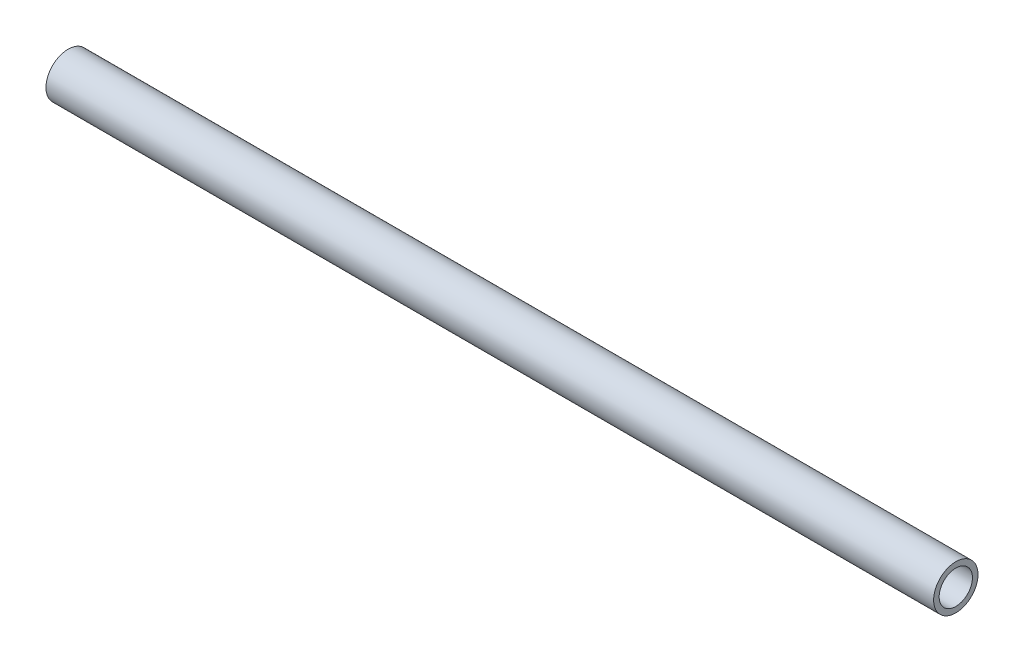
SolidWorks part; units mm, degrees
material "PVC 0.007 Plastificado"
ref_plane "Front" through (0, 0, 0) normal (0, 0, 1) x (1, 0, 0)
ref_plane "Top" through (0, 0, 0) normal (0, 1, 0) x (1, 0, 0)
ref_plane "Right" through (0, 0, 0) normal (1, 0, 0) x (0, 0, -1)
sketch "Sketch1" plane through (0, 0, 0) normal (1, 0, 0) x (0, 0, -1)
  line L0 (4.7625, 0) -> (6.35, 0) construction
  line L1 (4.7625, 0) -> (6.35, 0) construction
  line L2 (5.5562, 0) -> (5.5562, 1.0672) construction
  circle A0 centre (0, 0) radius 6.35
  circle A1 centre (0, 0) radius 4.7625
  point P4 (6.35, 0)
  point P5 (4.7625, 0)
  dimension "OD" = 12.7
  dimension "ID" = 9.525
  dimension "Wall Thickness" = 1.5875
sketch "Sketch2" plane through (0, 0, 0) normal (0, 0, 1) x (1, 0, 0)
  line L0 (-127, 0) -> (127, 0) construction
  point P2 (-111.125, 0)
  point P3 (111.125, 0)
  dimension "D1" = 15.875
  dimension "D2" = 15.875
sketch "Sketch3" plane through (0, 0, 0) normal (1, 0, 0) x (0, 0, -1)
  circle A0 centre (0, 0) radius 4.7625 construction
  circle A1 centre (0, 0) radius 6.35 construction
  circle A2 centre (0, 0) radius 4.7625
  circle A3 centre (0, 0) radius 6.35
extrude "Boss-Extrude1" add sketch "Sketch3" along normal mid plane 254
equation "\"D1@Boss-Extrude1\"=\"Length@Sketch2\""
equation "\"D1@Sketch2\"=\"OD@Sketch1\"*1.25"
equation "\"D2@Sketch2\"=\"D1@Sketch2\""
